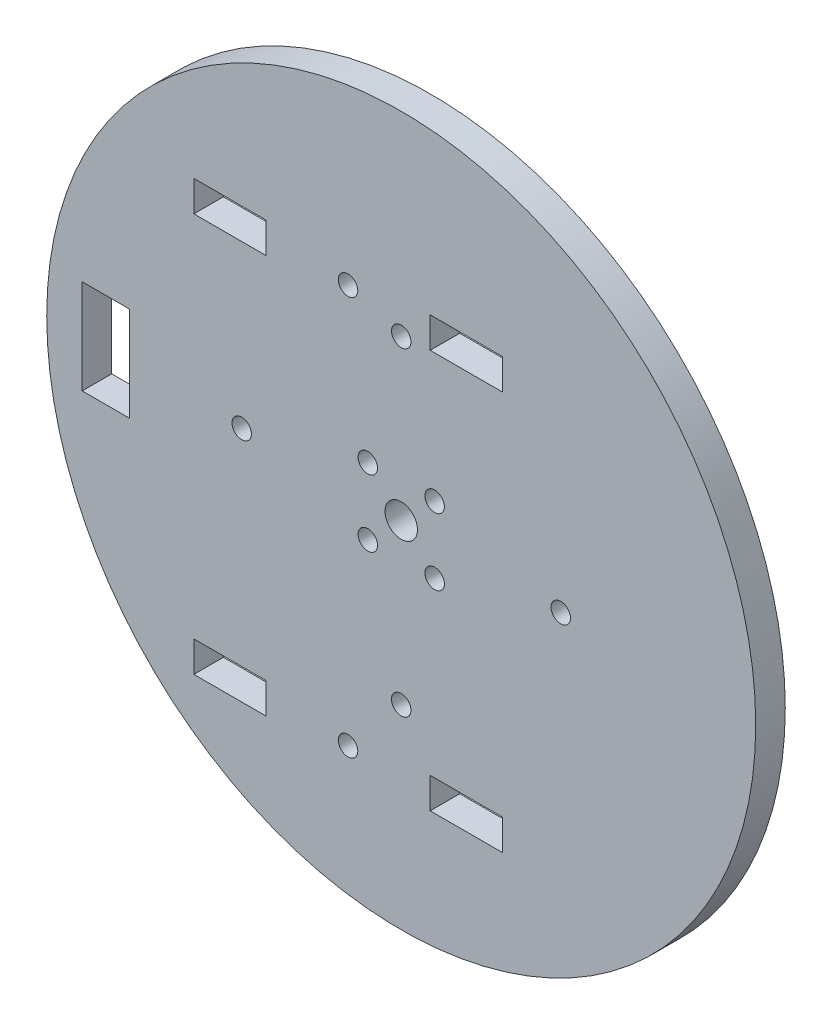
SolidWorks part; units mm, degrees
ref_plane "Спереди" through (0, 0, 0) normal (0, 0, 1) x (1, 0, 0)
ref_plane "Сверху" through (0, 0, 0) normal (0, 1, 0) x (1, 0, 0)
ref_plane "Справа" through (0, 0, 0) normal (1, 0, 0) x (0, 0, -1)
other "Configuration Table"
sketch "Eskiz_kontur" plane through (0, 0, 0) normal (0, 0, 1) x (1, 0, 0)
  line L0 (-22.9, -40.1) -> (-22.9, -34.9)
  line L1 (-22.9, -34.9) -> (-35.1, -34.9)
  line L2 (-35.1, -40.1) -> (-22.9, -40.1)
  line L3 (-35.1, -34.9) -> (-35.1, -40.1)
  line L4 (17.1, -40.1) -> (17.1, -34.9)
  line L5 (17.1, -34.9) -> (4.9, -34.9)
  line L6 (4.9, -40.1) -> (17.1, -40.1)
  line L7 (4.9, -34.9) -> (4.9, -40.1)
  line L8 (-46, -8) -> (-46, 8)
  line L9 (-46, 8) -> (-54, 8)
  line L10 (-54, 8) -> (-54, -8)
  line L11 (-54, -8) -> (-46, -8)
  line L12 (-22.9, 27.4) -> (-22.9, 32.6)
  line L13 (-22.9, 32.6) -> (-35.1, 32.6)
  line L14 (-35.1, 27.4) -> (-22.9, 27.4)
  line L15 (-35.1, 32.6) -> (-35.1, 27.4)
  line L16 (17.1, 27.4) -> (17.1, 32.6)
  line L17 (17.1, 32.6) -> (4.9, 32.6)
  line L18 (4.9, 27.4) -> (17.1, 27.4)
  line L19 (4.9, 32.6) -> (4.9, 27.4)
  circle A0 centre (0, 0) radius 60
extrude "Plastina" add sketch "Eskiz_kontur" along normal blind 5
sketch "Eskiz_otverstiya" plane through (0, 0, 0) normal (0, 0, 1) x (1, 0, 0)
  circle A0 centre (-9, -37.5) radius 1.65
  circle A1 centre (0, -27) radius 1.65
  circle A2 centre (-5.6569, -5.6569) radius 1.65
  circle A3 centre (5.6569, -5.6569) radius 1.65
  circle A4 centre (-27, 0) radius 1.65
  circle A5 centre (0, 0) radius 2.75
  circle A6 centre (-5.6569, 5.6569) radius 1.65
  circle A7 centre (5.6569, 5.6569) radius 1.65
  circle A8 centre (27, 0) radius 1.65
  circle A9 centre (-9, 30) radius 1.65
  circle A10 centre (0, 27) radius 1.65
  dimension "d1" = 3.3
  dimension "d2" = 3.3
  dimension "d3" = 3.3
  dimension "d4" = 3.3
  dimension "d5" = 3.3
  dimension "d6" = 5.5
  dimension "d7" = 3.3
  dimension "d8" = 3.3
  dimension "d9" = 3.3
  dimension "d10" = 3.3
  dimension "d11" = 3.3
extrude "Otverstiya" cut sketch "Eskiz_otverstiya" against normal through all and the other way through all
equation "\"T3\" = 3"
equation "\"T5\" = 5"
equation "\"D_M3\" = 3.3"
equation "\"D_M2\" = 2.2"
equation "\"D_M3_TAP\" = 2.5"
equation "\"D_M4\" = 4.5"
equation "\"L1\" = 100"
equation "\"L2\" = 100"
equation "\"D1@Plastina\" = \"T5\""
equation "\"d1@Eskiz_otverstiya\" = \"D_M3\""
equation "\"d2@Eskiz_otverstiya\" = \"D_M3\""
equation "\"d3@Eskiz_otverstiya\" = \"D_M3\""
equation "\"d4@Eskiz_otverstiya\" = \"D_M3\""
equation "\"d5@Eskiz_otverstiya\" = \"D_M3\""
equation "\"d7@Eskiz_otverstiya\" = \"D_M3\""
equation "\"d8@Eskiz_otverstiya\" = \"D_M3\""
equation "\"d9@Eskiz_otverstiya\" = \"D_M3\""
equation "\"d10@Eskiz_otverstiya\" = \"D_M3\""
equation "\"d11@Eskiz_otverstiya\" = \"D_M3\""
